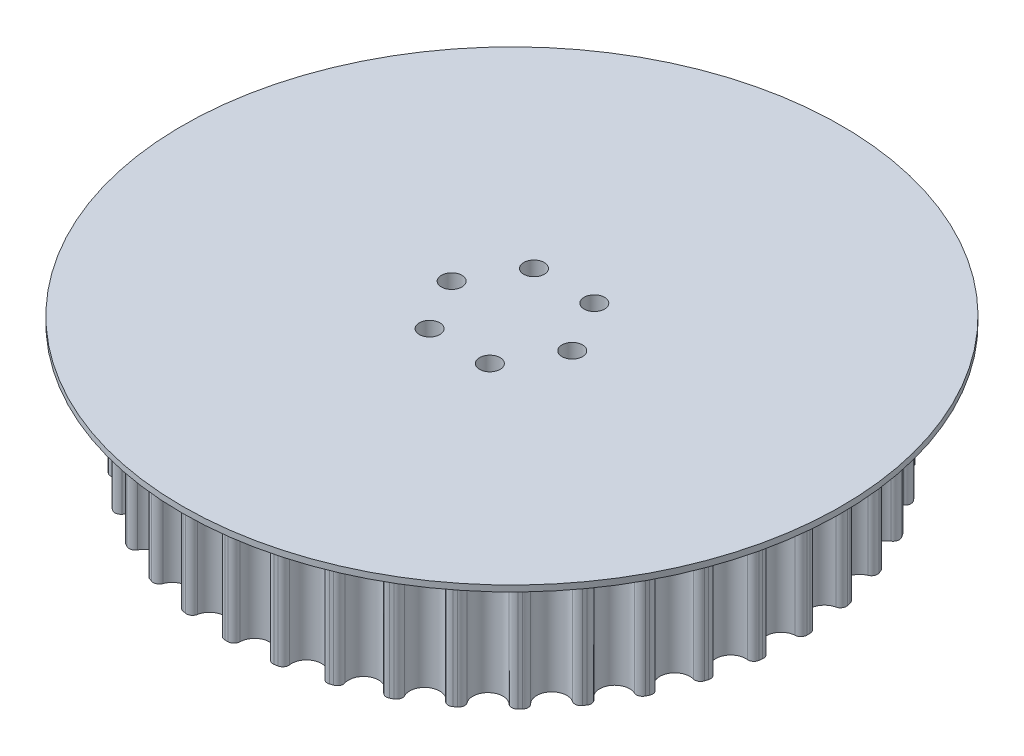
SolidWorks part; units mm, degrees
material "PETG"
ref_plane "Front Plane" through (0, 0, 0) normal (0, 0, 1) x (1, 0, 0)
ref_plane "Top Plane" through (0, 0, 0) normal (0, 1, 0) x (1, 0, 0)
ref_plane "Right Plane" through (0, 0, 0) normal (1, 0, 0) x (0, 0, -1)
sketch "Sketch5" plane through (0, 0, 0) normal (0, 1, 0) x (1, 0, 0)
  line L0 (0, 9.7022) -> (0, 50009.7022) construction
  line L1 (0, 0) -> (0, 46.5575) construction
  line L3 (0, 0) -> (-3.9957, 49.4953) construction
  line L5 (0, 0) -> (3.9957, 49.4953) construction
  circle A0 centre (0, 0) radius 49.6563 construction
  circle A2 centre (0, 0) radius 47.3449 construction
  arc A3 (-2.4772, 46.3129) -> (2.4772, 46.3129) centre (0, 46.5575) ccw
  arc A43 (3.8097, 47.1914) -> (3.5472, 47.2119) centre (0, 0) ccw
  arc A45 (-3.5472, 47.2119) -> (-3.8097, 47.1914) centre (0, 0) ccw
  arc A46 (-2.4772, 46.3129) -> (-3.5472, 47.2119) centre (-3.4723, 46.2147) ccw
  arc A47 (3.5472, 47.2119) -> (2.4772, 46.3129) centre (3.4723, 46.2147) ccw
  arc A48 (4.984, 46.1106) -> (9.8742, 45.3158) centre (7.4684, 45.9546) ccw
  arc A49 (4.984, 46.1106) -> (4.072, 47.1695) centre (3.986, 46.1732) ccw
  arc A50 (4.072, 47.1695) -> (3.8097, 47.1914) centre (0, 0) ccw
  arc A51 (11.0746, 46.0315) -> (9.8742, 45.3158) centre (10.8407, 45.0592) ccw
  arc A52 (11.3304, 45.9692) -> (11.0746, 46.0315) centre (0, 0) ccw
  arc A53 (12.3162, 44.714) -> (17.0155, 43.1451) centre (14.7433, 44.1615) ccw
  arc A54 (12.3162, 44.714) -> (11.5858, 45.9055) centre (11.3411, 44.9359) ccw
  arc A55 (11.5858, 45.9055) -> (11.3304, 45.9692) centre (0, 0) ccw
  arc A56 (18.3152, 43.6589) -> (17.0155, 43.1451) centre (17.9283, 42.7367) ccw
  arc A57 (18.5576, 43.5564) -> (18.3152, 43.6589) centre (0, 0) ccw
  arc A58 (19.3293, 42.1593) -> (23.7161, 39.8569) centre (21.6364, 41.2247) ccw
  arc A59 (19.3293, 42.1593) -> (18.7995, 43.4525) centre (18.4025, 42.5347) ccw
  arc A60 (18.7995, 43.4525) -> (18.5576, 43.5564) centre (0, 0) ccw
  arc A61 (25.0814, 40.1556) -> (23.7161, 39.8569) centre (24.5516, 39.3074) ccw
  arc A62 (25.3043, 40.0155) -> (25.0814, 40.1556) centre (0, 0) ccw
  arc A63 (25.8418, 38.5127) -> (29.8025, 35.5364) centre (27.9691, 37.2201) ccw
  arc A64 (25.8418, 38.5127) -> (25.5264, 39.8742) centre (24.9872, 39.032) ccw
  arc A65 (25.5264, 39.8742) -> (25.3043, 40.0155) centre (0, 0) ccw
  arc A66 (31.198, 35.6122) -> (29.8025, 35.5364) centre (30.539, 34.86) ccw
  arc A67 (31.3955, 35.4382) -> (31.198, 35.6122) centre (0, 0) ccw
  arc A68 (31.685, 33.8686) -> (35.117, 30.2956) centre (33.5774, 32.2515) ccw
  arc A69 (31.685, 33.8686) -> (31.5921, 35.2631) centre (30.9248, 34.5183) ccw
  arc A70 (31.5921, 35.2631) -> (31.3955, 35.4382) centre (0, 0) ccw
  arc A71 (36.5066, 30.1465) -> (35.117, 30.2956) centre (35.7355, 29.5098) ccw
  arc A72 (36.6736, 29.9431) -> (36.5066, 30.1465) centre (0, 0) ccw
  arc A73 (36.7076, 28.3474) -> (39.522, 24.2701) centre (38.3161, 26.4477) ccw
  arc A74 (36.7076, 28.3474) -> (36.8395, 29.7387) centre (36.0614, 29.1106) ccw
  arc A75 (36.8395, 29.7387) -> (36.6736, 29.9431) centre (0, 0) ccw
  arc A76 (40.8697, 23.9001) -> (39.522, 24.2701) centre (40.0064, 23.3953) ccw
  arc A77 (41.0019, 23.6725) -> (40.8697, 23.9001) centre (0, 0) ccw
  arc A78 (40.7795, 22.092) -> (42.9034, 17.616) centre (42.0624, 19.9589) ccw
  arc A79 (40.7795, 22.092) -> (41.1329, 23.4441) centre (40.2641, 22.949) ccw
  arc A80 (41.1329, 23.4441) -> (41.0019, 23.6725) centre (0, 0) ccw
  arc A81 (44.1743, 17.0346) -> (42.9034, 17.616) centre (43.2412, 16.6748) ccw
  arc A82 (44.2683, 16.7887) -> (44.1743, 17.0346) centre (0, 0) ccw
  arc A83 (43.7952, 15.2644) -> (45.1736, 10.5057) centre (44.7194, 12.9531) ccw
  arc A84 (43.7952, 15.2644) -> (44.361, 16.5424) centre (43.424, 16.193) ccw
  arc A85 (44.361, 16.5424) -> (44.2683, 16.7887) centre (0, 0) ccw
  arc A86 (46.3348, 9.728) -> (45.1736, 10.5057) centre (45.3561, 9.5225) ccw
  arc A87 (46.3881, 9.4702) -> (46.3348, 9.728) centre (0, 0) ccw
  arc A88 (45.6767, 8.0415) -> (46.2739, 3.1233) centre (46.2181, 5.6119) ccw
  arc A89 (45.6767, 8.0415) -> (46.4401, 9.2121) centre (45.4592, 9.0176) ccw
  arc A90 (46.4401, 9.2121) -> (46.3881, 9.4702) centre (0, 0) ccw
  arc A91 (47.2952, 2.1694) -> (46.2739, 3.1233) centre (46.2963, 2.1236) ccw
  arc A92 (47.3065, 1.9064) -> (47.2952, 2.1694) centre (0, 0) ccw
  arc A93 (46.3751, 0.6103) -> (46.1756, -4.34) centre (46.5198, -1.8747) ccw
  arc A94 (46.3751, 0.6103) -> (47.3164, 1.6433) centre (46.317, 1.6086) ccw
  arc A95 (47.3164, 1.6433) -> (47.3065, 1.9064) centre (0, 0) ccw
  arc A96 (47.0307, -5.4454) -> (46.1756, -4.34) centre (46.0374, -5.3304) ccw
  arc A97 (46.9997, -5.7068) -> (47.0307, -5.4454) centre (0, 0) ccw
  arc A98 (45.8725, -6.8367) -> (44.8815, -11.6909) centre (45.6166, -9.3127) ccw
  arc A99 (45.8725, -6.8367) -> (46.9673, -5.968) centre (45.9753, -5.842) ccw
  arc A100 (46.9673, -5.968) -> (46.9997, -5.7068) centre (0, 0) ccw
  arc A101 (45.5482, -12.9191) -> (44.8815, -11.6909) centre (44.5862, -12.6463) ccw
  arc A102 (45.4757, -13.1722) -> (45.5482, -12.9191) centre (0, 0) ccw
  arc A103 (44.1818, -14.1066) -> (42.4249, -18.739) centre (43.5321, -16.5095) ccw
  arc A104 (44.1818, -14.1066) -> (45.4017, -13.4248) centre (44.4428, -13.1413) ccw
  arc A105 (45.4017, -13.4248) -> (45.4757, -13.1722) centre (0, 0) ccw
  arc A106 (42.886, -20.0583) -> (42.4249, -18.739) centre (41.9802, -19.6346) ccw
  arc A107 (42.7738, -20.2964) -> (42.886, -20.0583) centre (0, 0) ccw
  arc A108 (41.3468, -21.0112) -> (38.8696, -25.3017) centre (40.32, -23.2788) ccw
  arc A109 (41.3468, -21.0112) -> (42.6603, -20.5339) centre (41.7592, -20.1002) ccw
  arc A110 (42.6603, -20.5339) -> (42.7738, -20.2964) centre (0, 0) ccw
  arc A111 (39.1131, -26.6779) -> (38.8696, -25.3017) centre (38.2869, -26.1145) ccw
  arc A112 (38.9641, -26.895) -> (39.1131, -26.6779) centre (0, 0) ccw
  arc A113 (37.4409, -27.3716) -> (34.3076, -31.2092) centre (36.0637, -29.4451) ccw
  arc A114 (37.4409, -27.3716) -> (38.814, -27.1112) centre (37.9942, -26.5386) ccw
  arc A115 (38.814, -27.1112) -> (38.9641, -26.895) centre (0, 0) ccw
  arc A116 (34.3271, -32.6066) -> (34.3076, -31.2092) centre (33.6021, -31.9179) ccw
  arc A117 (34.1453, -32.797) -> (34.3271, -32.6066) centre (0, 0) ccw
  arc A118 (32.5653, -33.0231) -> (28.857, -36.3084) centre (30.8734, -34.8488) ccw
  arc A119 (32.5653, -33.0231) -> (33.9624, -32.9863) centre (33.2451, -32.2896) ccw
  arc A120 (33.9624, -32.9863) -> (34.1453, -32.797) centre (0, 0) ccw
  arc A121 (28.6521, -37.6908) -> (28.857, -36.3084) centre (28.0469, -36.8948) ccw
  arc A122 (28.4421, -37.8496) -> (28.6521, -37.6908) centre (0, 0) ccw
  arc A123 (26.8464, -37.8193) -> (22.659, -40.4672) centre (24.8834, -39.35) ccw
  arc A124 (26.8464, -37.8193) -> (28.2312, -38.0071) centre (27.6349, -37.2044) ccw
  arc A125 (28.2312, -38.0071) -> (28.4421, -37.8496) centre (0, 0) ccw
  arc A126 (22.235, -41.7989) -> (22.659, -40.4672) centre (21.7654, -40.916) ccw
  arc A127 (22.0023, -41.9219) -> (22.235, -41.7989) centre (0, 0) ccw
  arc A128 (20.4321, -41.636) -> (15.8742, -43.5779) centre (18.249, -42.832) ccw
  arc A129 (20.4321, -41.636) -> (21.7689, -42.0436) centre (21.3091, -41.1555) ccw
  arc A130 (21.7689, -42.0436) -> (22.0023, -41.9219) centre (0, 0) ccw
  arc A131 (15.2421, -44.8243) -> (15.8742, -43.5779) centre (14.9202, -43.8776) ccw
  arc A132 (14.9926, -44.9084) -> (15.2421, -44.8243) centre (0, 0) ccw
  arc A133 (13.4886, -44.3744) -> (8.6782, -45.56) centre (11.1419, -45.2047) ccw
  arc A134 (13.4886, -44.3744) -> (14.7427, -44.9911) centre (14.4313, -44.0408) ccw
  arc A135 (14.7427, -44.9911) -> (14.9926, -44.9084) centre (0, 0) ccw
  arc A136 (7.8544, -46.6889) -> (8.6782, -45.56) centre (7.6885, -45.7027) ccw
  arc A137 (7.5947, -46.7318) -> (7.8544, -46.6889) centre (0, 0) ccw
  arc A138 (6.1958, -45.9634) -> (1.2575, -46.3621) centre (3.7463, -46.4066) ccw
  arc A139 (6.1958, -45.9634) -> (7.3347, -46.7733) centre (7.1798, -45.7854) ccw
  arc A140 (7.3347, -46.7733) -> (7.5947, -46.7318) centre (0, 0) ccw
  arc A141 (0.2632, -47.3442) -> (1.2575, -46.3621) centre (0.2577, -46.3442) ccw
  arc A142 (0, -47.3449) -> (0.2632, -47.3442) centre (0, 0) ccw
  arc A143 (-1.2575, -46.3621) -> (-6.1958, -45.9634) centre (-3.7463, -46.4066) ccw
  arc A144 (-1.2575, -46.3621) -> (-0.2632, -47.3442) centre (-0.2577, -46.3442) ccw
  arc A145 (-0.2632, -47.3442) -> (0, -47.3449) centre (0, 0) ccw
  arc A146 (-7.3347, -46.7733) -> (-6.1958, -45.9634) centre (-7.1798, -45.7854) ccw
  arc A147 (-7.5947, -46.7318) -> (-7.3347, -46.7733) centre (0, 0) ccw
  arc A148 (-8.6782, -45.56) -> (-13.4886, -44.3744) centre (-11.1419, -45.2047) ccw
  arc A149 (-8.6782, -45.56) -> (-7.8544, -46.6889) centre (-7.6885, -45.7027) ccw
  arc A150 (-7.8544, -46.6889) -> (-7.5947, -46.7318) centre (0, 0) ccw
  arc A151 (-14.7427, -44.9911) -> (-13.4886, -44.3744) centre (-14.4313, -44.0408) ccw
  arc A152 (-14.9926, -44.9084) -> (-14.7427, -44.9911) centre (0, 0) ccw
  arc A153 (-15.8742, -43.5779) -> (-20.4321, -41.636) centre (-18.249, -42.832) ccw
  arc A154 (-15.8742, -43.5779) -> (-15.2421, -44.8243) centre (-14.9202, -43.8776) ccw
  arc A155 (-15.2421, -44.8243) -> (-14.9926, -44.9084) centre (0, 0) ccw
  arc A156 (-21.7689, -42.0436) -> (-20.4321, -41.636) centre (-21.3091, -41.1555) ccw
  arc A157 (-22.0023, -41.9219) -> (-21.7689, -42.0436) centre (0, 0) ccw
  arc A158 (-22.659, -40.4672) -> (-26.8464, -37.8193) centre (-24.8834, -39.35) ccw
  arc A159 (-22.659, -40.4672) -> (-22.235, -41.7989) centre (-21.7654, -40.916) ccw
  arc A160 (-22.235, -41.7989) -> (-22.0023, -41.9219) centre (0, 0) ccw
  arc A161 (-28.2312, -38.0071) -> (-26.8464, -37.8193) centre (-27.6349, -37.2044) ccw
  arc A162 (-28.4421, -37.8496) -> (-28.2312, -38.0071) centre (0, 0) ccw
  arc A163 (-28.857, -36.3084) -> (-32.5653, -33.0231) centre (-30.8734, -34.8488) ccw
  arc A164 (-28.857, -36.3084) -> (-28.6521, -37.6908) centre (-28.0469, -36.8948) ccw
  arc A165 (-28.6521, -37.6908) -> (-28.4421, -37.8496) centre (0, 0) ccw
  arc A166 (-33.9624, -32.9863) -> (-32.5653, -33.0231) centre (-33.2451, -32.2896) ccw
  arc A167 (-34.1453, -32.797) -> (-33.9624, -32.9863) centre (0, 0) ccw
  arc A168 (-34.3076, -31.2092) -> (-37.4409, -27.3716) centre (-36.0637, -29.4451) ccw
  arc A169 (-34.3076, -31.2092) -> (-34.3271, -32.6066) centre (-33.6021, -31.9179) ccw
  arc A170 (-34.3271, -32.6066) -> (-34.1453, -32.797) centre (0, 0) ccw
  arc A171 (-38.814, -27.1112) -> (-37.4409, -27.3716) centre (-37.9942, -26.5386) ccw
  arc A172 (-38.9641, -26.895) -> (-38.814, -27.1112) centre (0, 0) ccw
  arc A173 (-38.8696, -25.3017) -> (-41.3468, -21.0112) centre (-40.32, -23.2788) ccw
  arc A174 (-38.8696, -25.3017) -> (-39.1131, -26.6779) centre (-38.2869, -26.1145) ccw
  arc A175 (-39.1131, -26.6779) -> (-38.9641, -26.895) centre (0, 0) ccw
  arc A176 (-42.6603, -20.5339) -> (-41.3468, -21.0112) centre (-41.7592, -20.1002) ccw
  arc A177 (-42.7738, -20.2964) -> (-42.6603, -20.5339) centre (0, 0) ccw
  arc A178 (-42.4249, -18.739) -> (-44.1818, -14.1066) centre (-43.5321, -16.5095) ccw
  arc A179 (-42.4249, -18.739) -> (-42.886, -20.0583) centre (-41.9802, -19.6346) ccw
  arc A180 (-42.886, -20.0583) -> (-42.7738, -20.2964) centre (0, 0) ccw
  arc A181 (-45.4017, -13.4248) -> (-44.1818, -14.1066) centre (-44.4428, -13.1413) ccw
  arc A182 (-45.4757, -13.1722) -> (-45.4017, -13.4248) centre (0, 0) ccw
  arc A183 (-44.8815, -11.6909) -> (-45.8725, -6.8367) centre (-45.6166, -9.3127) ccw
  arc A184 (-44.8815, -11.6909) -> (-45.5482, -12.9191) centre (-44.5862, -12.6463) ccw
  arc A185 (-45.5482, -12.9191) -> (-45.4757, -13.1722) centre (0, 0) ccw
  arc A186 (-46.9673, -5.968) -> (-45.8725, -6.8367) centre (-45.9753, -5.842) ccw
  arc A187 (-46.9997, -5.7068) -> (-46.9673, -5.968) centre (0, 0) ccw
  arc A188 (-46.1756, -4.34) -> (-46.3751, 0.6103) centre (-46.5198, -1.8747) ccw
  arc A189 (-46.1756, -4.34) -> (-47.0307, -5.4454) centre (-46.0374, -5.3304) ccw
  arc A190 (-47.0307, -5.4454) -> (-46.9997, -5.7068) centre (0, 0) ccw
  arc A191 (-47.3164, 1.6433) -> (-46.3751, 0.6103) centre (-46.317, 1.6086) ccw
  arc A192 (-47.3065, 1.9064) -> (-47.3164, 1.6433) centre (0, 0) ccw
  arc A193 (-46.2739, 3.1233) -> (-45.6767, 8.0415) centre (-46.2181, 5.6119) ccw
  arc A194 (-46.2739, 3.1233) -> (-47.2952, 2.1694) centre (-46.2963, 2.1236) ccw
  arc A195 (-47.2952, 2.1694) -> (-47.3065, 1.9064) centre (0, 0) ccw
  arc A196 (-46.4401, 9.2121) -> (-45.6767, 8.0415) centre (-45.4592, 9.0176) ccw
  arc A197 (-46.3881, 9.4702) -> (-46.4401, 9.2121) centre (0, 0) ccw
  arc A198 (-45.1736, 10.5057) -> (-43.7952, 15.2644) centre (-44.7194, 12.9531) ccw
  arc A199 (-45.1736, 10.5057) -> (-46.3348, 9.728) centre (-45.3561, 9.5225) ccw
  arc A200 (-46.3348, 9.728) -> (-46.3881, 9.4702) centre (0, 0) ccw
  arc A201 (-44.361, 16.5424) -> (-43.7952, 15.2644) centre (-43.424, 16.193) ccw
  arc A202 (-44.2683, 16.7887) -> (-44.361, 16.5424) centre (0, 0) ccw
  arc A203 (-42.9034, 17.616) -> (-40.7795, 22.092) centre (-42.0624, 19.9589) ccw
  arc A204 (-42.9034, 17.616) -> (-44.1743, 17.0346) centre (-43.2412, 16.6748) ccw
  arc A205 (-44.1743, 17.0346) -> (-44.2683, 16.7887) centre (0, 0) ccw
  arc A206 (-41.1329, 23.4441) -> (-40.7795, 22.092) centre (-40.2641, 22.949) ccw
  arc A207 (-41.0019, 23.6725) -> (-41.1329, 23.4441) centre (0, 0) ccw
  arc A208 (-39.522, 24.2701) -> (-36.7076, 28.3474) centre (-38.3161, 26.4477) ccw
  arc A209 (-39.522, 24.2701) -> (-40.8697, 23.9001) centre (-40.0064, 23.3953) ccw
  arc A210 (-40.8697, 23.9001) -> (-41.0019, 23.6725) centre (0, 0) ccw
  arc A211 (-36.8395, 29.7387) -> (-36.7076, 28.3474) centre (-36.0614, 29.1106) ccw
  arc A212 (-36.6736, 29.9431) -> (-36.8395, 29.7387) centre (0, 0) ccw
  arc A213 (-35.117, 30.2956) -> (-31.685, 33.8686) centre (-33.5774, 32.2515) ccw
  arc A214 (-35.117, 30.2956) -> (-36.5066, 30.1465) centre (-35.7355, 29.5098) ccw
  arc A215 (-36.5066, 30.1465) -> (-36.6736, 29.9431) centre (0, 0) ccw
  arc A216 (-31.5921, 35.2631) -> (-31.685, 33.8686) centre (-30.9248, 34.5183) ccw
  arc A217 (-31.3955, 35.4382) -> (-31.5921, 35.2631) centre (0, 0) ccw
  arc A218 (-29.8025, 35.5364) -> (-25.8418, 38.5127) centre (-27.9691, 37.2201) ccw
  arc A219 (-29.8025, 35.5364) -> (-31.198, 35.6122) centre (-30.539, 34.86) ccw
  arc A220 (-31.198, 35.6122) -> (-31.3955, 35.4382) centre (0, 0) ccw
  arc A221 (-25.5264, 39.8742) -> (-25.8418, 38.5127) centre (-24.9872, 39.032) ccw
  arc A222 (-25.3043, 40.0155) -> (-25.5264, 39.8742) centre (0, 0) ccw
  arc A223 (-23.7161, 39.8569) -> (-19.3293, 42.1593) centre (-21.6364, 41.2247) ccw
  arc A224 (-23.7161, 39.8569) -> (-25.0814, 40.1556) centre (-24.5516, 39.3074) ccw
  arc A225 (-25.0814, 40.1556) -> (-25.3043, 40.0155) centre (0, 0) ccw
  arc A226 (-18.7995, 43.4525) -> (-19.3293, 42.1593) centre (-18.4025, 42.5347) ccw
  arc A227 (-18.5576, 43.5564) -> (-18.7995, 43.4525) centre (0, 0) ccw
  arc A228 (-17.0155, 43.1451) -> (-12.3162, 44.714) centre (-14.7433, 44.1615) ccw
  arc A229 (-17.0155, 43.1451) -> (-18.3152, 43.6589) centre (-17.9283, 42.7367) ccw
  arc A230 (-18.3152, 43.6589) -> (-18.5576, 43.5564) centre (0, 0) ccw
  arc A231 (-11.5858, 45.9055) -> (-12.3162, 44.714) centre (-11.3411, 44.9359) ccw
  arc A232 (-11.3304, 45.9692) -> (-11.5858, 45.9055) centre (0, 0) ccw
  arc A233 (-9.8742, 45.3158) -> (-4.984, 46.1106) centre (-7.4684, 45.9546) ccw
  arc A234 (-9.8742, 45.3158) -> (-11.0746, 46.0315) centre (-10.8407, 45.0592) ccw
  arc A235 (-11.0746, 46.0315) -> (-11.3304, 45.9692) centre (0, 0) ccw
  arc A236 (-4.072, 47.1695) -> (-4.984, 46.1106) centre (-3.986, 46.1732) ccw
  arc A237 (-3.8097, 47.1914) -> (-4.072, 47.1695) centre (0, 0) ccw
  point P9 (0, 44.0683)
  point P14 (0, 49.6563)
  point P31 (0, 47.3449)
  dimension "D3" = 2.4892
  dimension "D4" = 99.3127
  dimension "D6" = 1
  dimension "D2" = 5.588
  dimension "D1" = 3.2766
  dimension "D5" = 8
  dimension "D7" = 39
extrude "Boss-Extrude3" add sketch "Sketch5" along normal mid plane 22
sketch "Sketch2" plane through (0, 11, 0) normal (0, 1, 0) x (1, 0, 0)
  circle A0 centre (0, 0) radius 54.6563
  dimension "D1" = 109.3127
extrude "Boss-Extrude2" add sketch "Sketch2" along normal blind 1
sketch "Sketch3" plane through (0, 12, 0) normal (0, 1, 0) x (1, 0, 0)
  line L0 (0, 0) -> (10, 0) construction
  circle A0 centre (10, 0) radius 1.7
  circle A1 centre (5, -8.6603) radius 1.7
  circle A2 centre (-5, -8.6603) radius 1.7
  circle A3 centre (-10, 0) radius 1.7
  circle A4 centre (-5, 8.6603) radius 1.7
  circle A5 centre (5, 8.6603) radius 1.7
  dimension "D1" = 10
  dimension "D2" = 3.4
  dimension "D3" = 6
extrude "Cut-Extrude1" cut sketch "Sketch3" against normal through all
sketch "Sketch4" plane through (0, -11, 0) normal (0, 1, 0) x (1, 0, 0)
  line L0 (0, 0) -> (5, -8.6603) construction
  circle A0 centre (5, -8.6603) radius 3
  circle A1 centre (-5, -8.6603) radius 3
  circle A2 centre (-10, 0) radius 3
  circle A3 centre (-5, 8.6603) radius 3
  circle A4 centre (5, 8.6603) radius 3
  circle A5 centre (10, 0) radius 3
  dimension "D1" = 6
  dimension "D2" = 6
extrude "Cut-Extrude2" cut sketch "Sketch4" along normal offset from surface (13 mm away) 10 up to face at (10, 12, 1.7)
sketch "Sketch6" plane through (0, -11, 0) normal (0, -1, 0) x (1, 0, 0)
  line L0 (0, 0) -> (35, 0) construction
  circle A0 centre (35, 0) radius 1.985
  circle A1 centre (-17.5, -30.3109) radius 1.985
  circle A2 centre (-17.5, 30.3109) radius 1.985
  dimension "D2" = 3.97
  dimension "D1" = 35
  dimension "D3" = 3
extrude "Cut-Extrude3" cut sketch "Sketch6" against normal blind 20
equation "\"pitch\"= 8mm"
equation "\"n\"= 39"
equation "\"pitch_dia\"= \"pitch\" * \"n\" / PI"
equation "\"belt_width\"= 22mm"
equation "\"D1@Sketch2\"=\"pitch_dia\"+10.00mm"
equation "\"D4@Sketch5\"=\"pitch_dia\""
equation "\"D1@Boss-Extrude3\" = \"belt_width\""
equation "\"D7@Sketch5\"=\"n\""
equation "\"D5@Sketch5\"=\"pitch\""
equation "\"tol_dia_id_intfc\" = 0.0200mm ' For hole diameters - Interference fit"
equation "\"tol_dia_id_slip\"  = 0.0300mm ' For hole diameters - Slip fit"
equation "\"tol_dia_id_clear\" = 0.0500mm ' For hole diameters - Clearance fit"
equation "\"tol_dia_od_intfc\" = 0.0200mm ' For shaft diameters - Interference fit"
equation "\"tol_dia_od_slip\"  = 0.0300mm ' For shaft diameters - Slip fit"
equation "\"tol_dia_od_clear\" = 0.0500mm ' For shaft diameters - Clearance fit"
equation "\"tol_general_intfc\"= 0.0030mm ' For general parts (Horiz) - Interference fit"
equation "\"tol_general_slip\" = 0.0050mm ' For general parts (Horiz) - Slip fit"
equation "\"tol_general_clear\"= 0.0100mm ' For general parts (Horiz) - Clearance fit"
equation "\"tol_layer_intfc\"  = 0.0030mm ' For all parts (Vert) - Interference fit"
equation "\"tol_layer_slip\"   = 0.0050mm ' For all parts (Vert) - Slip fit"
equation "\"tol_layer_clear\"  = 0.0100mm ' For all parts (Vert) - Clearance fit"
equation "\"tol_corner_rad\"   = 0.100mm ' For corners that fit into other parts"
equation "\"D2@Sketch6\"=3.95+\"tol_dia_id_intfc\""
